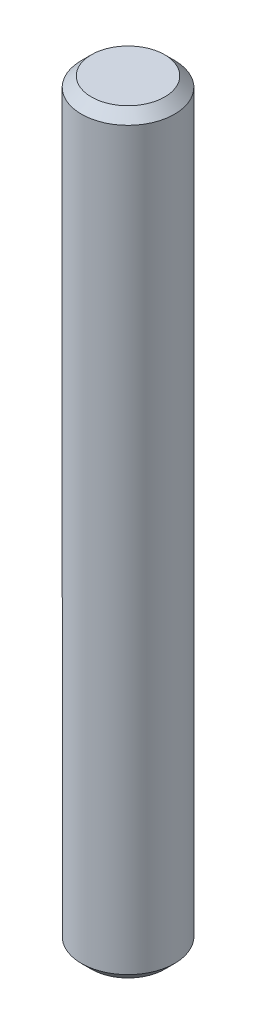
SolidWorks part; units mm, degrees
ref_plane "Front Plane" through (0, 0, 0) normal (0, 0, 1) x (1, 0, 0)
ref_plane "Top Plane" through (0, 0, 0) normal (0, 1, 0) x (1, 0, 0)
ref_plane "Right Plane" through (0, 0, 0) normal (1, 0, 0) x (0, 0, -1)
sketch "Sketch1" plane through (0, 0, 0) normal (0, 1, 0) x (1, 0, 0)
  circle A0 centre (0, 0) radius 2.975
  dimension "D1" = 5.95
extrude "Boss-Extrude1" add sketch "Sketch1" along normal blind 48.26
chamfer "Chamfer1" distance 0.635 angle 45 2 edges at (0, 0, 2.975) (0, 48.26, 2.975)
